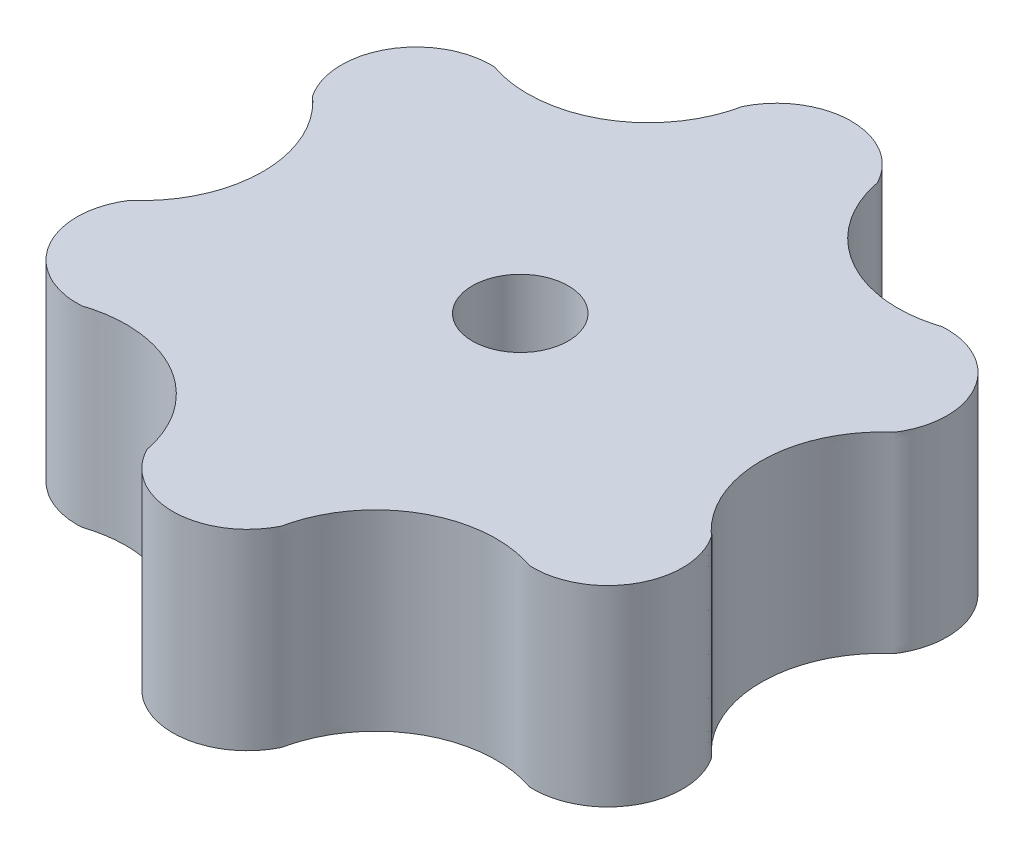
SolidWorks part; units mm, degrees
ref_plane "前视基准面" through (0, 0, 0) normal (0, 0, 1) x (1, 0, 0)
ref_plane "上视基准面" through (0, 0, 0) normal (0, 1, 0) x (1, 0, 0)
ref_plane "右视基准面" through (0, 0, 0) normal (1, 0, 0) x (0, 0, -1)
sketch "草图2" plane through (0, 0, 0) normal (0, -1, 0) x (1, 0, 0)
  spline S2 degree 3 poles (-0.0746, -0.0121) (0.0005, -0.0025) (0.0736, 0.0172) (0.1472, 0.0344) (0.2576, 0.0602) (0.368, 0.086) (0.5887, 0.1376) (0.732, 0.1865) (0.9487, 0.2533) (1.0214, 0.274) (1.1624, 0.3285) (1.3034, 0.383) (1.4444, 0.4375) (1.5854, 0.492) (1.6529, 0.5263) (1.8581, 0.6227) (1.9969, 0.6829) (2.2608, 0.8305) (2.3927, 0.9043) (2.5576, 0.9966) (2.5882, 1.0189) (2.6514, 1.0603) (2.7462, 1.1226) (2.8567, 1.1951) (2.9357, 1.247) (2.9673, 1.2677) (2.9838, 1.2771) (3.0288, 1.3115) (3.119, 1.3803) (3.2391, 1.4719) (3.3293, 1.5407) (3.3894, 1.5865) (3.4203, 1.6084) (3.5054, 1.6833) (3.6188, 1.7832) (3.7322, 1.8831) (3.8173, 1.958) (3.8457, 1.983) (3.8988, 2.0368) (3.9784, 2.1175) (4.058, 2.1982) (4.1642, 2.3058) (4.218, 2.3588) (4.3657, 2.5309) (4.4642, 2.6456) (4.5872, 2.7889) (4.6091, 2.8198) (4.6543, 2.8804) (4.722, 2.9713) (4.7898, 3.0621) (4.9253, 3.2439) (5.0046, 3.3728) (5.1275, 3.5633) (5.1698, 3.626) (5.2431, 3.7582) (5.3164, 3.8904) (5.3897, 4.0226) (5.4355, 4.1052) (5.437, 4.1246) (5.4448, 4.1616) (5.4567, 4.217) (5.4685, 4.2724) (5.5078, 4.4572) (5.5374, 4.6055) (5.6137, 4.8981) (5.6495, 5.045) (5.7746, 5.4808) (5.869, 5.7682) (6.1787, 6.6206) (6.4267, 7.1737) (6.7852, 7.839) (6.862, 7.9692) (6.9748, 8.1659) (7.0111, 8.2323) (7.0928, 8.3595) (7.1336, 8.4231) (7.2562, 8.6138) (7.3355, 8.7426) (7.5109, 8.9888) (7.5986, 9.1119) (7.774, 9.3581) (7.87, 9.4751) (8.0108, 9.6527) (8.0578, 9.7119) (8.1517, 9.8303) (8.2019, 9.887) (8.3518, 10.057) (8.4498, 10.1722) (8.6044, 10.338) (8.6557, 10.3936) (8.7614, 10.5016) (8.8143, 10.5556) (9.0787, 10.8255) (9.3006, 11.0312) (9.5859, 11.2789) (9.6419, 11.3298) (9.7585, 11.4259) (9.8168, 11.474) (9.9334, 11.5702) (9.9942, 11.6153) (10.1134, 11.7081) (10.1731, 11.7546) (10.3519, 11.8939) (10.4773, 11.9786) (10.6633, 12.1081) (10.7254, 12.1513) (10.8494, 12.2377) (10.9131, 12.2784) (11.1032, 12.402) (11.2333, 12.479) (11.4268, 12.5972) (11.4922, 12.6349) (11.6237, 12.7096) (11.6888, 12.7479) (11.889, 12.8544) (12.0218, 12.9267) (12.2253, 13.0267) (12.2931, 13.0601) (12.4287, 13.1268) (12.4974, 13.1582) (12.6349, 13.221) (12.7036, 13.2527) (12.8429, 13.3112) (12.9126, 13.3404) (13.1217, 13.4281) (13.2611, 13.4869) (13.5463, 13.5872) (13.6889, 13.6373) (13.9741, 13.7375) (14.1196, 13.7788) (14.4102, 13.862) (14.5548, 13.906) (14.7745, 13.9623) (14.8487, 13.977) (14.9962, 14.01) (15.1437, 14.0431) (15.2912, 14.0761) (15.4387, 14.1091) (15.5137, 14.1191) (15.7373, 14.1564) (15.8864, 14.1813) (16.1846, 14.231) (16.3355, 14.2431) (16.636, 14.2755) (16.7862, 14.2942) (17.0881, 14.3095) (17.2391, 14.3171) (17.541, 14.3324) (17.6922, 14.3313) (17.9189, 14.3301) (17.9945, 14.3297) (18.1457, 14.3288) (18.2212, 14.3248) (18.4478, 14.3169) (18.5986, 14.3063) (18.8249, 14.2925) (18.9, 14.2837) (19.0505, 14.2702) (19.1258, 14.2631) (19.2759, 14.2457) (19.3512, 14.2383) (19.5008, 14.2167) (19.5756, 14.2059) (19.8, 14.1736) (19.9494, 14.1507) (20.2459, 14.0918) (20.3947, 14.0649) (20.6897, 13.9987) (20.8359, 13.9602) (21.0557, 13.9045) (21.1292, 13.8868) (21.2748, 13.8462) (21.3466, 13.8226) (21.4911, 13.7782) (21.5994, 13.7448) (21.7258, 13.7059) (21.78, 13.6892) (21.8071, 13.6809) (21.8169, 13.6829) (21.8358, 13.6823) (21.9963, 13.6774) (22.1568, 13.6726) (22.3457, 13.6668) (22.3835, 13.6703) (22.459, 13.673) (22.5723, 13.6771) (22.6856, 13.6812) (22.7988, 13.6853) (22.8366, 13.6866) (22.9118, 13.6944) (23.0245, 13.7062) (23.1749, 13.7218) (23.2876, 13.7336) (23.3628, 13.7414) (23.4001, 13.7476) (23.5117, 13.7671) (23.6607, 13.793) (23.8096, 13.819) (23.9212, 13.8385) (23.9576, 13.8491) (24.031, 13.8672) (24.141, 13.8944) (24.2511, 13.9216) (24.3611, 13.9487) (24.3984, 13.9558) (24.4703, 13.979) (24.5782, 14.0138) (24.7221, 14.0602) (24.83, 14.095) (24.9019, 14.1182) (24.9381, 14.1291) (25.1134, 14.1996) (25.2536, 14.256) (25.4289, 14.3265) (25.4638, 14.341) (25.5318, 14.3741) (25.6337, 14.4237) (25.7356, 14.4734) (25.8715, 14.5395) (25.94, 14.5716) (26.0709, 14.6472) (26.2018, 14.7228) (26.3326, 14.7984) (26.4635, 14.874) (26.5248, 14.9185) (26.7126, 15.0455) (26.8404, 15.1267) (27.0783, 15.3132) (27.1972, 15.4065) (27.3459, 15.5231) (27.3724, 15.5502) (27.4285, 15.6009) (27.5126, 15.6769) (27.5967, 15.7529) (27.7649, 15.905) (27.867, 16.0166) (28.0242, 16.18) (28.0781, 16.2331) (28.1752, 16.3489) (28.2724, 16.4648) (28.3695, 16.5806) (28.4666, 16.6964) (28.5088, 16.7593) (28.5978, 16.8814) (28.6424, 16.9425) (28.7091, 17.0341) (28.7329, 17.0636) (28.7733, 17.1275) (28.8338, 17.2233) (28.8944, 17.3192) (28.9751, 17.447) (29.0163, 17.5104) (29.1244, 17.7097) (29.1965, 17.8425) (29.2776, 17.992) (29.2844, 18.0097) (29.3002, 18.044) (29.3238, 18.0956) (29.379, 18.2158) (29.4263, 18.3188) (29.4736, 18.4218) (29.4892, 18.4562) (29.516, 18.5269) (29.5562, 18.6329) (29.6098, 18.7742) (29.6501, 18.8802) (29.6769, 18.9508) (29.7097, 19.0593) (29.7645, 19.2402) (29.8083, 19.3848) (29.8411, 19.4933) (29.8476, 19.5307) (29.8645, 19.6044) (29.8897, 19.7149) (29.915, 19.8254) (29.9402, 19.9359) (29.9503, 19.9724) (29.962, 20.0471) (29.9794, 20.1591) (29.9969, 20.2711) (30.0202, 20.4205) (30.0348, 20.4948) (30.0539, 20.7207) (30.0666, 20.8713) (30.0825, 21.0596) (30.0849, 21.0973) (30.0859, 21.1729) (30.0875, 21.2862) (30.089, 21.3996) (30.091, 21.5507) (30.0929, 21.6263) (30.0843, 21.7772) (30.0756, 21.9281) (30.067, 22.079) (30.0583, 22.2299) (30.0458, 22.3046) (30.0169, 22.5295) (30.0015, 22.68) (29.9419, 22.9764) (29.9121, 23.1246) (29.8786, 23.2913) (29.8723, 23.3092) (29.8623, 23.3457) (29.8473, 23.4003) (29.8122, 23.5278) (29.7821, 23.6371) (29.722, 23.8557) (29.6679, 23.9971) (29.5928, 24.211) (29.5693, 24.2829) (29.5095, 24.4218) (29.4498, 24.5606) (29.39, 24.6994) (29.3302, 24.8383) (29.2928, 24.9041) (29.2238, 25.0386) (29.1892, 25.1058) (29.1375, 25.2067) (29.1216, 25.241) (29.0827, 25.3058) (29.0243, 25.403) (28.9465, 25.5326) (28.8881, 25.6298) (28.8589, 25.6784) (28.8514, 25.6964) (28.8233, 25.7217) (28.697, 25.8355) (28.5707, 25.9494) (28.4023, 26.1012) (28.3494, 26.1553) (28.2419, 26.2615) (28.1881, 26.3146) (28.0267, 26.4738) (27.9236, 26.5844) (27.4108, 27.1395) (27.0327, 27.6132) (26.6045, 28.236) (26.5233, 28.3635) (26.3998, 28.5536) (26.36, 28.6179) (26.2806, 28.7465) (26.2443, 28.8128) (26.1304, 29.0088) (26.053, 29.1388) (25.9144, 29.4074) (25.8451, 29.5418) (25.7412, 29.7433) (25.7105, 29.8124) (25.6478, 29.9499) (25.6164, 30.0186) (25.5536, 30.1561) (25.5205, 30.2241) (25.4615, 30.3633) (25.434, 30.4337) (25.3506, 30.6445) (25.293, 30.7843) (25.1895, 31.0684) (25.1431, 31.2122) (25.0467, 31.4987) (25.0036, 31.6437) (24.9426, 31.862) (24.9223, 31.9348) (24.8817, 32.0804) (24.8644, 32.154) (24.8279, 32.3007) (24.8105, 32.3742) (24.7776, 32.5218) (24.7595, 32.5952) (24.7164, 32.8178) (24.686, 32.9659) (24.6484, 33.1895) (24.6356, 33.264) (24.6148, 33.4137) (24.6044, 33.4885) (24.5732, 33.7131) (24.5545, 33.8631) (24.5354, 34.089) (24.529, 34.1643) (24.5162, 34.3149) (24.5081, 34.3901) (24.5, 34.5411) (24.4955, 34.6165) (24.4886, 34.7675) (24.4882, 34.8431) (24.4845, 34.9942) (24.4826, 35.0698) (24.4789, 35.2209) (24.4813, 35.2965) (24.4828, 35.5232) (24.4892, 35.6742) (24.4971, 35.9008) (24.503, 35.9762) (24.513, 36.127) (24.5171, 36.2025) (24.5351, 36.4285) (24.5515, 36.5788) (24.5896, 36.8787) (24.6076, 37.0288) (24.6541, 37.3275) (24.6832, 37.4758) (24.725, 37.6987) (24.7372, 37.7733) (24.7692, 37.921) (24.7856, 37.9948) (24.8405, 38.2148) (24.8771, 38.3614) (24.9504, 38.6547) (24.9953, 38.7991) (25.0607, 39.0162) (25.0829, 39.0884) (25.1305, 39.2319) (25.1531, 39.304) (25.2326, 39.5164) (25.2857, 39.6579) (25.3652, 39.8702) (25.3905, 39.9415) (25.4478, 40.0813) (25.4791, 40.1501) (25.5402, 40.2884) (25.5708, 40.3575) (25.6319, 40.4958) (25.6612, 40.5655) (25.759, 40.77) (25.8285, 40.9042) (25.9663, 41.1733) (26.0353, 41.3079) (26.1879, 41.5688) (26.2617, 41.7009) (26.3818, 41.8932) (26.4218, 41.9573) (26.5019, 42.0855) (26.5448, 42.1477) (26.6282, 42.2738) (26.6698, 42.3369) (26.7568, 42.4605) (26.8003, 42.5223) (26.9307, 42.7078) (27.0217, 42.8285) (27.2086, 43.0661) (27.3018, 43.1851) (27.4947, 43.4179) (27.5959, 43.5302) (27.7454, 43.7007) (27.796, 43.7568) (27.8984, 43.868) (27.9522, 43.9211) (28.1103, 44.0836) (28.2133, 44.1945) (28.4347, 44.4003) (28.5593, 44.516) (28.6908, 44.6382) (28.7116, 44.6575) (28.7254, 44.6703) (28.7306, 44.6782) (28.7554, 44.7184) (28.8151, 44.8148) (28.8946, 44.9433) (28.9542, 45.0397) (28.994, 45.104) (29.0121, 45.1372) (29.0652, 45.2373) (29.136, 45.3709) (29.2067, 45.5044) (29.251, 45.5879) (29.2576, 45.6057) (29.273, 45.6402) (29.2961, 45.6919) (29.35, 45.8127) (29.3962, 45.9162) (29.4424, 46.0198) (29.4581, 46.0542) (29.4841, 46.1251) (29.5231, 46.2316) (29.562, 46.338) (29.614, 46.48) (29.641, 46.5506) (29.704, 46.7684) (29.746, 46.9136) (29.809, 47.1314) (29.8217, 47.2061) (29.8534, 47.3539) (29.8773, 47.4647) (29.9011, 47.5755) (29.9169, 47.6494) (29.9204, 47.6872) (29.9363, 47.7994) (29.9523, 47.9117) (29.9682, 48.0239) (29.9788, 48.0987) (29.9864, 48.1359) (29.9944, 48.249) (30.005, 48.3998) (30.0157, 48.5505) (30.0236, 48.6636) (30.0275, 48.7013) (30.0275, 48.7768) (30.0275, 48.8902) (30.0274, 49.0036) (30.0274, 49.1547) (30.0302, 49.2304) (30.0141, 49.4566) (30.0034, 49.6073) (29.9873, 49.8335) (29.9757, 49.9082) (29.9544, 50.0578) (29.9384, 50.1701) (29.9224, 50.2823) (29.9117, 50.3571) (29.9042, 50.3941) (29.8804, 50.505) (29.8486, 50.6528) (29.8169, 50.8005) (29.7931, 50.9114) (29.7814, 50.9474) (29.7605, 51.02) (29.7291, 51.1289) (29.6977, 51.2379) (29.6662, 51.3468) (29.6577, 51.3837) (29.6318, 51.4547) (29.593, 51.5612) (29.5542, 51.6677) (29.5024, 51.8098) (29.4786, 51.8816) (29.3867, 52.0889) (29.3254, 52.227) (29.2335, 52.4343) (29.1955, 52.4998) (29.1252, 52.6336) (29.09, 52.7005) (28.9845, 52.9012) (28.902, 53.0281) (28.8033, 53.1891) (28.7835, 53.2214) (28.744, 53.2858) (28.7222, 53.3167) (28.6567, 53.4091) (28.5911, 53.5016) (28.5255, 53.5941) (28.4818, 53.6558) (28.4618, 53.688) (28.3901, 53.7758) (28.2946, 53.8929) (28.199, 54.01) (28.1273, 54.0979) (28.1034, 54.1271) (28.0517, 54.1823) (27.9742, 54.265) (27.8708, 54.3752) (27.7933, 54.4579) (27.7416, 54.5131) (27.7144, 54.5393) (27.5759, 54.6678) (27.4651, 54.7706) (27.3266, 54.8992) (27.2966, 54.9222) (27.2377, 54.9696) (27.1495, 55.0407) (27.0318, 55.1356) (26.9435, 55.2067) (26.8846, 55.2541) (26.8523, 55.2739) (26.7592, 55.3386) (26.6661, 55.4033) (26.5731, 55.4681) (26.511, 55.5112) (26.481, 55.5344) (26.3836, 55.5924) (26.2538, 55.6697) (26.1239, 55.7471) (26.0265, 55.8051) (25.9945, 55.8252) (25.9269, 55.8592) (25.8257, 55.9101) (25.7244, 55.9611) (25.5894, 56.029) (25.5229, 56.0653) (25.3137, 56.1527) (25.1742, 56.2109) (24.965, 56.2983) (24.893, 56.3212) (24.7497, 56.3695) (24.6423, 56.4057) (24.5349, 56.4419) (24.4633, 56.4661) (24.4267, 56.4756) (24.317, 56.5042) (24.1708, 56.5424) (24.0245, 56.5805) (23.9148, 56.6092) (23.8773, 56.6146) (23.803, 56.6286) (23.6916, 56.6495) (23.5802, 56.6704) (23.4688, 56.6914) (23.4319, 56.7) (23.3569, 56.7089) (23.2443, 56.7221) (23.1317, 56.7354) (22.9816, 56.753) (22.9067, 56.7637) (22.6802, 56.7749) (22.5292, 56.7824) (22.3405, 56.7917) (22.3027, 56.7901) (22.2272, 56.7888) (22.1138, 56.7868) (21.9816, 56.7845) (21.8777, 56.7827) (21.8494, 56.7822) (21.8352, 56.782) (21.8309, 56.7793) (21.8219, 56.7763) (21.7815, 56.7632) (21.6692, 56.7268) (21.5613, 56.6918) (21.4175, 56.6452) (21.3457, 56.6216) (21.2009, 56.5784) (21.1276, 56.5598) (20.909, 56.4997) (20.7634, 56.4589) (20.4685, 56.3923) (20.3213, 56.3577) (19.8767, 56.2688) (19.578, 56.221) (18.9783, 56.1442) (18.677, 56.1184) (18.2241, 56.0945) (18.0732, 56.0861) (17.8464, 56.0855) (17.7709, 56.0852) (17.6197, 56.0848) (17.5441, 56.083) (17.3174, 56.0877) (17.1665, 56.0971) (16.9778, 56.106) (16.9401, 56.1078) (16.8646, 56.1114) (16.8268, 56.1122) (16.7139, 56.123) (16.5634, 56.1374) (16.413, 56.1518) (16.2625, 56.1662) (16.1871, 56.172) (15.9628, 56.2052) (15.8133, 56.2273) (15.5142, 56.2716) (15.366, 56.3016) (15.1438, 56.3464) (15.0697, 56.3614) (14.9215, 56.3912) (14.8482, 56.4098) (14.7009, 56.4438) (14.6281, 56.464) (14.4817, 56.5016) (14.4082, 56.5194) (14.1903, 56.5819) (14.0452, 56.6244) (13.6126, 56.7603) (13.3273, 56.861) (12.9072, 57.0316) (12.7669, 57.0879) (12.559, 57.1784) (12.491, 57.2114) (12.3542, 57.2757) (12.2858, 57.3078) (12.0806, 57.4042) (11.9451, 57.4713) (11.6796, 57.616) (11.5455, 57.6858) (11.3499, 57.8005) (11.2847, 57.8387) (11.1543, 57.9151) (11.0908, 57.9561) (10.9626, 58.0362) (10.8977, 58.075) (10.7721, 58.1591) (10.7093, 58.2012) (10.5837, 58.2853) (10.5209, 58.3273) (10.3978, 58.415) (10.3362, 58.4588) (10.213, 58.5464) (10.1541, 58.5939) (10.0338, 58.6853) (9.9736, 58.7311) (9.7931, 58.8682) (9.6782, 58.9665) (9.4488, 59.1634) (9.3328, 59.2605) (9.109, 59.4637) (9.0022, 59.5707) (8.8392, 59.7283) (8.7848, 59.7808) (8.6761, 59.8858) (8.6258, 59.9423) (8.4723, 60.1092) (8.3699, 60.2204) (8.1652, 60.4428) (8.071, 60.5611) (7.9269, 60.7362) (7.8789, 60.7945) (7.7828, 60.9112) (7.7345, 60.9694) (7.6008, 61.1525) (7.5116, 61.2745) (7.3778, 61.4576) (7.334, 61.5191) (7.2485, 61.6438) (7.2081, 61.7077) (7.0849, 61.898) (7.0018, 62.0243) (6.8452, 62.2829) (6.7712, 62.4147) (6.6215, 62.6773) (6.5495, 62.8103) (6.4483, 63.0132) (6.4145, 63.0808) (6.347, 63.2161) (6.3152, 63.2846) (6.2516, 63.4217) (6.2183, 63.4896) (6.1583, 63.6283) (6.1283, 63.6977) (6.0382, 63.9058) (5.9848, 64.0473) (5.8726, 64.328) (5.8252, 64.4716) (5.728, 64.7578) (5.6779, 64.9006) (5.5956, 65.1915) (5.5545, 65.3369) (5.4927, 65.5551) (5.4762, 65.6288) (5.4425, 65.7762) (5.4087, 65.9235) (5.375, 66.0709) (5.356, 66.1537) (5.3541, 66.163) (5.3452, 66.1797) (5.3318, 66.2046) (5.3005, 66.2629) (5.2379, 66.3794) (5.1842, 66.4792) (5.1305, 66.5791) (5.113, 66.6126) (5.0729, 66.6766) (5.0127, 66.7727) (4.9324, 66.9008) (4.8722, 66.9968) (4.8321, 67.0609) (4.81, 67.0915) (4.6991, 67.2445) (4.6103, 67.3668) (4.4994, 67.5198) (4.4734, 67.5474) (4.4249, 67.6054) (4.3522, 67.6923) (4.2795, 67.7793) (4.1341, 67.9533) (4.0262, 68.0594) (3.8691, 68.2229) (3.8181, 68.2789) (3.706, 68.3802) (3.5939, 68.4816) (3.4818, 68.583) (3.3697, 68.6844) (3.309, 68.7295) (3.19, 68.8228) (3.1008, 68.8927) (3.0115, 68.9626) (2.9521, 69.0093) (2.9205, 69.0301) (2.7639, 69.1358) (2.6387, 69.2204) (2.4821, 69.3262) (2.4486, 69.3438) (2.3831, 69.3816) (2.285, 69.4383) (2.154, 69.5138) (2.0558, 69.5704) (2.0067, 69.5988) (1.9892, 69.606) (1.9552, 69.6225) (1.8703, 69.6638) (1.7513, 69.7217) (1.6494, 69.7712) (1.5814, 69.8043) (1.5481, 69.8224) (1.4429, 69.8646) (1.3027, 69.921) (1.1624, 69.9774) (1.0572, 70.0196) (1.0223, 70.0341) (0.9504, 70.0573) (0.8425, 70.0921) (0.7346, 70.1269) (0.5907, 70.1733) (0.5192, 70.1978) (0.2991, 70.2523) (0.1524, 70.2887) (-0.0677, 70.3432) (-0.1428, 70.3532) (-0.2917, 70.3793) (-0.3661, 70.3924) (-0.5894, 70.4317) (-0.7401, 70.4449) (-0.9655, 70.4689) (-1.0406, 70.4788) (-1.1916, 70.4848) (-1.3426, 70.4908) (-1.4936, 70.4968) (-1.6069, 70.5013) (-1.6447, 70.4988) (-1.7203, 70.4968) (-1.8336, 70.4938) (-1.9469, 70.4908) (-2.0602, 70.4878) (-2.098, 70.4869) (-2.1733, 70.4798) (-2.2861, 70.4693) (-2.4366, 70.4552) (-2.5495, 70.4447) (-2.6247, 70.4376) (-2.662, 70.4314) (-2.8485, 70.4011) (-2.9977, 70.3769) (-3.1656, 70.3496) (-3.1837, 70.3441) (-3.2205, 70.3355) (-3.2757, 70.3226) (-3.4045, 70.2925) (-3.5149, 70.2667) (-3.7357, 70.2151) (-3.8789, 70.1661) (-4.0956, 70.0994) (-4.1684, 70.0787) (-4.3093, 70.0242) (-4.4503, 69.9697) (-4.5913, 69.9152) (-4.7323, 69.8607) (-4.7998, 69.8264) (-5.005, 69.73) (-5.1439, 69.6697) (-5.4077, 69.5221) (-5.5396, 69.4483) (-5.7045, 69.3561) (-5.7351, 69.3338) (-5.7983, 69.2923) (-5.8931, 69.2301) (-6.0036, 69.1575) (-6.0826, 69.1057) (-6.1142, 69.085) (-6.1307, 69.0755) (-6.1757, 69.0412) (-6.2659, 68.9724) (-6.3861, 68.8807) (-6.4762, 68.812) (-6.5363, 68.7662) (-6.5672, 68.7443) (-6.6523, 68.6694) (-6.7657, 68.5695) (-6.8791, 68.4696) (-6.9642, 68.3946) (-6.9926, 68.3697) (-7.0457, 68.3159) (-7.1253, 68.2352) (-7.2049, 68.1545) (-7.3111, 68.0469) (-7.365, 67.9938) (-7.5126, 67.8218) (-7.6111, 67.7071) (-7.7341, 67.5637) (-7.756, 67.5329) (-7.8012, 67.4723) (-7.869, 67.3814) (-7.9367, 67.2905) (-8.0723, 67.1088) (-8.1516, 66.9799) (-8.2745, 66.7894) (-8.3168, 66.7267) (-8.3901, 66.5945) (-8.4634, 66.4623) (-8.5367, 66.3301) (-8.5825, 66.2475) (-8.5839, 66.2281) (-8.5918, 66.1911) (-8.6036, 66.1357) (-8.6154, 66.0802) (-8.6548, 65.8955) (-8.6843, 65.7471) (-8.7606, 65.4546) (-8.7964, 65.3077) (-8.9215, 64.8719) (-9.0159, 64.5845) (-9.3256, 63.7321) (-9.5737, 63.179) (-9.9321, 62.5137) (-10.009, 62.3835) (-10.1217, 62.1868) (-10.158, 62.1204) (-10.2397, 61.9932) (-10.2805, 61.9296) (-10.4031, 61.7388) (-10.4824, 61.6101) (-10.6578, 61.3639) (-10.7455, 61.2407) (-10.9209, 60.9945) (-11.0169, 60.8776) (-11.1578, 60.7) (-11.2047, 60.6408) (-11.2987, 60.5223) (-11.3488, 60.4657) (-11.4987, 60.2956) (-11.5968, 60.1805) (-11.7514, 60.0147) (-11.8026, 59.9591) (-11.9084, 59.8511) (-11.9612, 59.7971) (-12.2257, 59.5271) (-12.4475, 59.3215) (-12.7329, 59.0737) (-12.7888, 59.0229) (-12.9054, 58.9267) (-12.9637, 58.8786) (-13.0803, 58.7824) (-13.1411, 58.7374) (-13.2603, 58.6445) (-13.32, 58.5981) (-13.4989, 58.4588) (-13.6242, 58.3741) (-13.8103, 58.2446) (-13.8723, 58.2014) (-13.9963, 58.115) (-14.06, 58.0743) (-14.2501, 57.9507) (-14.3802, 57.8737) (-14.5737, 57.7555) (-14.6392, 57.7177) (-14.7706, 57.643) (-14.8357, 57.6047) (-15.036, 57.4983) (-15.1687, 57.426) (-15.3722, 57.3259) (-15.44, 57.2926) (-15.5756, 57.2259) (-15.6444, 57.1945) (-15.7818, 57.1316) (-15.8505, 57.1) (-15.9899, 57.0415) (-16.0595, 57.0123) (-16.2686, 56.9245) (-16.408, 56.8657) (-16.6932, 56.7655) (-16.8358, 56.7154) (-17.121, 56.6152) (-17.2665, 56.5739) (-17.5571, 56.4907) (-17.7018, 56.4466) (-17.9214, 56.3903) (-17.9956, 56.3757) (-18.1431, 56.3426) (-18.2906, 56.3096) (-18.4381, 56.2766) (-18.5856, 56.2435) (-18.6606, 56.2335) (-18.8842, 56.1962) (-19.0333, 56.1714) (-19.3315, 56.1217) (-19.4824, 56.1095) (-19.7829, 56.0771) (-19.9331, 56.0585) (-20.235, 56.0432) (-20.386, 56.0356) (-20.6879, 56.0203) (-20.8391, 56.0213) (-21.0659, 56.0226) (-21.1414, 56.023) (-21.2926, 56.0238) (-21.3681, 56.0279) (-21.5947, 56.0357) (-21.7455, 56.0464) (-21.9718, 56.0601) (-22.0469, 56.069) (-22.1975, 56.0825) (-22.2727, 56.0896) (-22.4228, 56.1069) (-22.4981, 56.1143) (-22.6477, 56.1359) (-22.7225, 56.1467) (-22.9469, 56.1791) (-23.0963, 56.202) (-23.3929, 56.2609) (-23.5417, 56.2877) (-23.8366, 56.3539) (-23.9828, 56.3925) (-24.2026, 56.4481) (-24.2761, 56.4659) (-24.4217, 56.5065) (-24.4935, 56.53) (-24.638, 56.5745) (-24.7463, 56.6078) (-24.8727, 56.6467) (-24.9269, 56.6634) (-24.954, 56.6717) (-24.9638, 56.6697) (-24.9827, 56.6703) (-25.1432, 56.6752) (-25.3038, 56.6801) (-25.4926, 56.6859) (-25.5304, 56.6824) (-25.6059, 56.6797) (-25.7192, 56.6756) (-25.8325, 56.6715) (-25.9458, 56.6673) (-25.9835, 56.6661) (-26.0587, 56.6583) (-26.1715, 56.6465) (-26.3218, 56.6308) (-26.4345, 56.619) (-26.5097, 56.6112) (-26.547, 56.605) (-26.6587, 56.5856) (-26.8076, 56.5596) (-26.9565, 56.5337) (-27.0682, 56.5142) (-27.1045, 56.5036) (-27.1779, 56.4854) (-27.2879, 56.4583) (-27.398, 56.4311) (-27.5081, 56.4039) (-27.5453, 56.3969) (-27.6172, 56.3737) (-27.7251, 56.3389) (-27.869, 56.2925) (-27.9769, 56.2577) (-28.0488, 56.2345) (-28.085, 56.2235) (-28.2603, 56.153) (-28.4005, 56.0966) (-28.5758, 56.0261) (-28.6107, 56.0116) (-28.6787, 55.9785) (-28.7806, 55.9289) (-28.8825, 55.8793) (-29.0184, 55.8131) (-29.0869, 55.7811) (-29.2178, 55.7055) (-29.3487, 55.6299) (-29.4796, 55.5542) (-29.6104, 55.4786) (-29.6717, 55.4342) (-29.8595, 55.3072) (-29.9873, 55.226) (-30.2252, 55.0394) (-30.3441, 54.9462) (-30.4928, 54.8296) (-30.5194, 54.8025) (-30.5754, 54.7518) (-30.6595, 54.6758) (-30.7436, 54.5997) (-30.9118, 54.4477) (-31.0139, 54.336) (-31.1711, 54.1727) (-31.2251, 54.1196) (-31.3222, 54.0037) (-31.4193, 53.8879) (-31.5164, 53.7721) (-31.6135, 53.6563) (-31.6557, 53.5934) (-31.7448, 53.4712) (-31.7893, 53.4102) (-31.8561, 53.3186) (-31.8799, 53.2891) (-31.9202, 53.2252) (-31.9808, 53.1293) (-32.0413, 53.0335) (-32.122, 52.9057) (-32.1632, 52.8423) (-32.2713, 52.643) (-32.3434, 52.5101) (-32.4245, 52.3607) (-32.4313, 52.343) (-32.4471, 52.3086) (-32.4708, 52.2571) (-32.5259, 52.1369) (-32.5732, 52.0339) (-32.6205, 51.9309) (-32.6361, 51.8965) (-32.6629, 51.8258) (-32.7031, 51.7198) (-32.7568, 51.5785) (-32.797, 51.4725) (-32.8238, 51.4018) (-32.8567, 51.2933) (-32.9114, 51.1125) (-32.9552, 50.9678) (-32.9881, 50.8593) (-32.9946, 50.822) (-33.0114, 50.7483) (-33.0367, 50.6378) (-33.0619, 50.5273) (-33.0872, 50.4168) (-33.0973, 50.3803) (-33.1089, 50.3056) (-33.1264, 50.1936) (-33.1438, 50.0816) (-33.1671, 49.9322) (-33.1818, 49.8579) (-33.2008, 49.632) (-33.2136, 49.4814) (-33.2294, 49.2931) (-33.2319, 49.2554) (-33.2329, 49.1798) (-33.2344, 49.0665) (-33.2359, 48.9531) (-33.238, 48.802) (-33.2399, 48.7264) (-33.2312, 48.5755) (-33.2226, 48.4246) (-33.2139, 48.2737) (-33.2052, 48.1228) (-33.1928, 48.0481) (-33.1638, 47.8232) (-33.1485, 47.6726) (-33.0889, 47.3763) (-33.0591, 47.2281) (-33.0256, 47.0614) (-33.0193, 47.0435) (-33.0093, 47.007) (-32.9942, 46.9524) (-32.9592, 46.8249) (-32.9291, 46.7155) (-32.869, 46.4969) (-32.8149, 46.3556) (-32.7397, 46.1417) (-32.7162, 46.0698) (-32.6565, 45.9309) (-32.5967, 45.7921) (-32.5369, 45.6532) (-32.4772, 45.5144) (-32.4397, 45.4486) (-32.3707, 45.3141) (-32.3362, 45.2468) (-32.2844, 45.146) (-32.2685, 45.1116) (-32.2296, 45.0468) (-32.1712, 44.9497) (-32.0934, 44.8201) (-32.035, 44.7229) (-32.0058, 44.6743) (-31.9984, 44.6563) (-31.9703, 44.631) (-31.844, 44.5171) (-31.7177, 44.4033) (-31.5493, 44.2515) (-31.4964, 44.1974) (-31.3888, 44.0912) (-31.335, 44.0381) (-31.1737, 43.8788) (-31.0706, 43.7683) (-30.5577, 43.2131) (-30.1797, 42.7395) (-29.7515, 42.1167) (-29.6703, 41.9892) (-29.5467, 41.7991) (-29.507, 41.7348) (-29.4276, 41.6062) (-29.3913, 41.5399) (-29.2773, 41.3439) (-29.1999, 41.2139) (-29.0614, 40.9452) (-28.9921, 40.8109) (-28.8882, 40.6094) (-28.8575, 40.5403) (-28.7947, 40.4028) (-28.7633, 40.3341) (-28.7006, 40.1966) (-28.6675, 40.1286) (-28.6085, 39.9894) (-28.5809, 39.919) (-28.4975, 39.7082) (-28.4399, 39.5684) (-28.3365, 39.2843) (-28.2873, 39.1414) (-28.1478, 38.7099) (-28.0662, 38.4187) (-27.9748, 38.052) (-27.9574, 37.9785) (-27.9245, 37.8309) (-27.9064, 37.7575) (-27.8633, 37.5349) (-27.8329, 37.3868) (-27.7954, 37.1632) (-27.7826, 37.0887) (-27.7618, 36.939) (-27.7514, 36.8642) (-27.7202, 36.6396) (-27.7015, 36.4896) (-27.6823, 36.2637) (-27.6759, 36.1884) (-27.6632, 36.0378) (-27.655, 35.9626) (-27.647, 35.8116) (-27.6424, 35.7362) (-27.6355, 35.5852) (-27.6352, 35.5096) (-27.6314, 35.3585) (-27.6296, 35.2829) (-27.6258, 35.1318) (-27.6283, 35.0562) (-27.6298, 34.8295) (-27.6361, 34.6785) (-27.6441, 34.4519) (-27.6499, 34.3765) (-27.66, 34.2257) (-27.6641, 34.1502) (-27.682, 33.9242) (-27.6984, 33.7739) (-27.7365, 33.474) (-27.7545, 33.3239) (-27.8011, 33.0252) (-27.8301, 32.8769) (-27.872, 32.654) (-27.8841, 32.5794) (-27.9162, 32.4317) (-27.9325, 32.3579) (-27.9874, 32.1379) (-28.0241, 31.9913) (-28.079, 31.7713) (-28.0985, 31.6983) (-28.1437, 31.554) (-28.1888, 31.4098) (-28.234, 31.2655) (-28.2791, 31.1213) (-28.3001, 31.0486) (-28.3796, 30.8363) (-28.4326, 30.6947) (-28.5121, 30.4824) (-28.5375, 30.4112) (-28.5948, 30.2713) (-28.626, 30.2025) (-28.6872, 30.0642) (-28.7177, 29.9951) (-28.7788, 29.8569) (-28.8081, 29.7872) (-28.906, 29.5826) (-28.9755, 29.4484) (-29.1132, 29.1793) (-29.1823, 29.0448) (-29.3349, 28.7838) (-29.4086, 28.6518) (-29.5287, 28.4595) (-29.5688, 28.3954) (-29.6488, 28.2672) (-29.6918, 28.2049) (-29.7752, 28.0788) (-29.8168, 28.0158) (-29.9037, 27.8921) (-29.9472, 27.8303) (-30.0777, 27.6449) (-30.1686, 27.5241) (-30.3556, 27.2866) (-30.4488, 27.1675) (-30.6417, 26.9348) (-30.7429, 26.8225) (-30.8923, 26.652) (-30.943, 26.5958) (-31.0454, 26.4847) (-31.0992, 26.4315) (-31.2573, 26.269) (-31.3602, 26.1581) (-31.5817, 25.9524) (-31.7063, 25.8366) (-31.8378, 25.7145) (-31.8585, 25.6952) (-31.8724, 25.6823) (-31.8775, 25.6744) (-31.9024, 25.6343) (-31.962, 25.5379) (-32.0415, 25.4093) (-32.1012, 25.3129) (-32.141, 25.2486) (-32.159, 25.2155) (-32.2121, 25.1153) (-32.2829, 24.9818) (-32.3537, 24.8482) (-32.3979, 24.7647) (-32.4046, 24.747) (-32.42, 24.7125) (-32.4431, 24.6607) (-32.497, 24.5399) (-32.5432, 24.4364) (-32.5893, 24.3329) (-32.6051, 24.2985) (-32.631, 24.2275) (-32.67, 24.1211) (-32.709, 24.0146) (-32.761, 23.8727) (-32.7879, 23.802) (-32.8509, 23.5842) (-32.8929, 23.439) (-32.9559, 23.2212) (-32.9686, 23.1465) (-33.0004, 22.9988) (-33.0242, 22.8879) (-33.048, 22.7771) (-33.0639, 22.7032) (-33.0673, 22.6654) (-33.0833, 22.5532) (-33.0992, 22.441) (-33.1152, 22.3287) (-33.1258, 22.2539) (-33.1334, 22.2167) (-33.1413, 22.1037) (-33.152, 21.9529) (-33.1626, 21.8021) (-33.1706, 21.689) (-33.1745, 21.6514) (-33.1744, 21.5758) (-33.1744, 21.4624) (-33.1744, 21.3491) (-33.1743, 21.1979) (-33.1771, 21.1222) (-33.161, 20.8961) (-33.1503, 20.7453) (-33.1342, 20.5192) (-33.1226, 20.4444) (-33.1013, 20.2948) (-33.0853, 20.1826) (-33.0693, 20.0703) (-33.0587, 19.9955) (-33.0511, 19.9585) (-33.0273, 19.8477) (-32.9956, 19.6999) (-32.9638, 19.5521) (-32.9401, 19.4412) (-32.9284, 19.4052) (-32.9074, 19.3326) (-32.876, 19.2237) (-32.8446, 19.1148) (-32.8132, 19.0059) (-32.8046, 18.9689) (-32.7787, 18.8979) (-32.7399, 18.7914) (-32.7011, 18.6849) (-32.6493, 18.5429) (-32.6255, 18.4711) (-32.5336, 18.2638) (-32.4724, 18.1256) (-32.3805, 17.9183) (-32.3425, 17.8528) (-32.2721, 17.719) (-32.237, 17.6521) (-32.1315, 17.4514) (-32.049, 17.3246) (-31.9502, 17.1635) (-31.9304, 17.1313) (-31.8909, 17.0669) (-31.8692, 17.036) (-31.8036, 16.9435) (-31.738, 16.851) (-31.6724, 16.7585) (-31.6287, 16.6969) (-31.6087, 16.6646) (-31.5371, 16.5768) (-31.4415, 16.4597) (-31.3459, 16.3426) (-31.2742, 16.2548) (-31.2503, 16.2255) (-31.1986, 16.1704) (-31.1211, 16.0877) (-31.0177, 15.9774) (-30.9402, 15.8947) (-30.8885, 15.8396) (-30.8613, 15.8134) (-30.7228, 15.6848) (-30.612, 15.582) (-30.4736, 15.4535) (-30.4435, 15.4305) (-30.3847, 15.3831) (-30.2964, 15.3119) (-30.1787, 15.2171) (-30.0904, 15.146) (-30.0316, 15.0986) (-29.9992, 15.0788) (-29.9061, 15.0141) (-29.8131, 14.9493) (-29.72, 14.8846) (-29.658, 14.8414) (-29.628, 14.8182) (-29.5306, 14.7602) (-29.4007, 14.6829) (-29.2708, 14.6056) (-29.1734, 14.5476) (-29.1414, 14.5275) (-29.0739, 14.4935) (-28.9726, 14.4425) (-28.8713, 14.3916) (-28.7363, 14.3236) (-28.6699, 14.2873) (-28.4607, 14.2) (-28.3212, 14.1417) (-28.112, 14.0543) (-28.0399, 14.0314) (-27.8966, 13.9831) (-27.7892, 13.9469) (-27.6818, 13.9107) (-27.6102, 13.8866) (-27.5736, 13.877) (-27.4639, 13.8484) (-27.3177, 13.8103) (-27.1714, 13.7721) (-27.0617, 13.7435) (-27.0242, 13.738) (-26.95, 13.7241) (-26.8386, 13.7031) (-26.7271, 13.6822) (-26.6157, 13.6613) (-26.5788, 13.6526) (-26.5038, 13.6438) (-26.3912, 13.6305) (-26.2786, 13.6173) (-26.1285, 13.5996) (-26.0536, 13.5889) (-25.8271, 13.5778) (-25.6762, 13.5703) (-25.4875, 13.561) (-25.4497, 13.5626) (-25.3741, 13.5639) (-25.2608, 13.5659) (-25.1285, 13.5682) (-25.0246, 13.57) (-24.9963, 13.5704) (-24.9821, 13.5707) (-24.9778, 13.5734) (-24.9688, 13.5763) (-24.9284, 13.5894) (-24.8161, 13.6259) (-24.7082, 13.6609) (-24.5645, 13.7075) (-24.4927, 13.7311) (-24.3478, 13.7743) (-24.2745, 13.7929) (-24.0559, 13.853) (-23.9103, 13.8938) (-23.6154, 13.9604) (-23.4683, 13.9949) (-23.0236, 14.0839) (-22.725, 14.1317) (-22.1252, 14.2085) (-21.8239, 14.2343) (-21.3711, 14.2582) (-21.2201, 14.2665) (-20.9934, 14.2672) (-20.9178, 14.2674) (-20.7666, 14.2679) (-20.691, 14.2696) (-20.4644, 14.265) (-20.3135, 14.2556) (-20.1247, 14.2466) (-20.087, 14.2448) (-20.0115, 14.2412) (-19.9737, 14.2405) (-19.8608, 14.2297) (-19.7104, 14.2153) (-19.5599, 14.2009) (-19.4094, 14.1865) (-19.334, 14.1806) (-19.1097, 14.1474) (-18.9602, 14.1253) (-18.6612, 14.0811) (-18.513, 14.051) (-18.2907, 14.0062) (-18.2166, 13.9913) (-18.0685, 13.9614) (-17.9951, 13.9429) (-17.8479, 13.9089) (-17.775, 13.8887) (-17.6286, 13.8511) (-17.5551, 13.8333) (-17.3372, 13.7708) (-17.1922, 13.7282) (-16.7595, 13.5924) (-16.4743, 13.4916) (-16.0541, 13.3211) (-15.9138, 13.2648) (-15.7059, 13.1742) (-15.638, 13.1412) (-15.5011, 13.077) (-15.4327, 13.0448) (-15.2275, 12.9485) (-15.092, 12.8813) (-14.8266, 12.7367) (-14.6924, 12.6669) (-14.4968, 12.5522) (-14.4317, 12.5139) (-14.3013, 12.4375) (-14.2377, 12.3965) (-14.1095, 12.3164) (-14.0446, 12.2777) (-13.919, 12.1935) (-13.8562, 12.1515) (-13.7307, 12.0674) (-13.6679, 12.0253) (-13.5447, 11.9377) (-13.4831, 11.8939) (-13.36, 11.8062) (-13.3011, 11.7588) (-13.1807, 11.6673) (-13.1206, 11.6216) (-12.94, 11.4844) (-12.8251, 11.3861) (-12.5957, 11.1892) (-12.4798, 11.0922) (-12.256, 10.8889) (-12.1491, 10.7819) (-11.9861, 10.6244) (-11.9318, 10.5718) (-11.8231, 10.4668) (-11.7728, 10.4103) (-11.6192, 10.2435) (-11.5169, 10.1323) (-11.3121, 9.9098) (-11.2179, 9.7915) (-11.0738, 9.6165) (-11.0258, 9.5581) (-10.9297, 9.4414) (-10.8815, 9.3832) (-10.7477, 9.2001) (-10.6585, 9.0781) (-10.5247, 8.895) (-10.4809, 8.8335) (-10.3954, 8.7088) (-10.355, 8.645) (-10.2318, 8.4546) (-10.1487, 8.3283) (-9.9921, 8.0697) (-9.9181, 7.9379) (-9.7684, 7.6753) (-9.6964, 7.5423) (-9.5952, 7.3394) (-9.5615, 7.2718) (-9.494, 7.1366) (-9.4621, 7.0681) (-9.3985, 6.9309) (-9.3653, 6.863) (-9.3052, 6.7243) (-9.2752, 6.6549) (-9.1851, 6.4469) (-9.1318, 6.3054) (-9.0196, 6.0247) (-8.9721, 5.881) (-8.8749, 5.5948) (-8.8249, 5.4521) (-8.7425, 5.1612) (-8.7014, 5.0157) (-8.6397, 4.7976) (-8.6231, 4.7238) (-8.5894, 4.5765) (-8.5557, 4.4291) (-8.522, 4.2818) (-8.503, 4.1989) (-8.5011, 4.1896) (-8.4921, 4.173) (-8.4787, 4.148) (-8.4474, 4.0898) (-8.3848, 3.9733) (-8.3311, 3.8734) (-8.2775, 3.7735) (-8.26, 3.74) (-8.2198, 3.676) (-8.1596, 3.5799) (-8.0794, 3.4519) (-8.0192, 3.3558) (-7.979, 3.2918) (-7.9569, 3.2611) (-7.846, 3.1082) (-7.7572, 2.9858) (-7.6463, 2.8329) (-7.6203, 2.8053) (-7.5718, 2.7473) (-7.4991, 2.6603) (-7.4264, 2.5733) (-7.281, 2.3993) (-7.1731, 2.2932) (-7.016, 2.1297) (-6.9651, 2.0738) (-6.8529, 1.9724) (-6.7408, 1.871) (-6.6287, 1.7696) (-6.5166, 1.6683) (-6.4559, 1.6231) (-6.3369, 1.5299) (-6.2477, 1.4599) (-6.1585, 1.39) (-6.099, 1.3434) (-6.0674, 1.3226) (-5.9109, 1.2168) (-5.7856, 1.1322) (-5.629, 1.0265) (-5.5955, 1.0088) (-5.5301, 0.971) (-5.4319, 0.9144) (-5.3009, 0.8389) (-5.2027, 0.7822) (-5.1537, 0.7539) (-5.1361, 0.7467) (-5.1021, 0.7301) (-5.0172, 0.6888) (-4.8982, 0.631) (-4.7963, 0.5814) (-4.7283, 0.5484) (-4.695, 0.5303) (-4.5898, 0.488) (-4.4496, 0.4317) (-4.3093, 0.3753) (-4.2041, 0.333) (-4.1692, 0.3186) (-4.0973, 0.2954) (-3.9894, 0.2606) (-3.8815, 0.2258) (-3.7377, 0.1793) (-3.6661, 0.1548) (-3.446, 0.1003) (-3.2993, 0.064) (-3.0792, 0.0095) (-3.0041, -0.0005) (-2.8553, -0.0267) (-2.7808, -0.0398) (-2.5575, -0.0791) (-2.4068, -0.0922) (-2.1814, -0.1163) (-2.1064, -0.1262) (-1.9553, -0.1322) (-1.8043, -0.1381) (-1.6533, -0.1441) (-1.54, -0.1486) (-1.5022, -0.1461) (-1.4267, -0.1441) (-1.3133, -0.1411) (-1.2, -0.1381) (-1.0867, -0.1351) (-1.0489, -0.1342) (-0.9737, -0.1272) (-0.8608, -0.1166) (-0.7103, -0.1026) (-0.5974, -0.092) (-0.5222, -0.085) (-0.4849, -0.0787) (-0.373, -0.0605) (-0.2611, -0.0424) (-0.1492, -0.0242) (-0.0746, -0.0121) (0.0005, -0.0025) (0.0736, 0.0172) knots -0.000977 -0.000488 -0.000488 0 0.000488 0.000488 0.000977 0.001953 0.001953 0.003906 0.003906 0.004883 0.004883 0.005859 0.006836 0.006836 0.007813 0.007813 0.009766 0.009766 0.011719 0.011719 0.012207 0.012207 0.012695 0.013672 0.013916 0.013916 0.01416 0.01416 0.014648 0.015625 0.016113 0.016113 0.016602 0.016602 0.017578 0.018555 0.018555 0.019043 0.019043 0.019531 0.020508 0.020508 0.021484 0.021484 0.023438 0.023438 0.023926 0.023926 0.024414 0.025391 0.025391 0.027344 0.027344 0.02832 0.02832 0.029297 0.030273 0.030273 0.030518 0.030518 0.030762 0.03125 0.03125 0.033203 0.033203 0.035156 0.035156 0.039063 0.039063 0.046875 0.046875 0.048828 0.048828 0.049805 0.049805 0.050781 0.050781 0.052734 0.052734 0.054688 0.054688 0.056641 0.056641 0.057617 0.057617 0.058594 0.058594 0.060547 0.060547 0.061523 0.061523 0.0625 0.0625 0.066406 0.066406 0.067383 0.067383 0.068359 0.068359 0.069336 0.069336 0.070313 0.070313 0.072266 0.072266 0.073242 0.073242 0.074219 0.074219 0.076172 0.076172 0.077148 0.077148 0.078125 0.078125 0.080078 0.080078 0.081055 0.081055 0.082031 0.082031 0.083008 0.083008 0.083984 0.083984 0.085938 0.085938 0.087891 0.087891 0.089844 0.089844 0.091797 0.091797 0.092773 0.092773 0.09375 0.094727 0.094727 0.095703 0.095703 0.097656 0.097656 0.099609 0.099609 0.101563 0.101563 0.103516 0.103516 0.105469 0.105469 0.106445 0.106445 0.107422 0.107422 0.109375 0.109375 0.110352 0.110352 0.111328 0.111328 0.112305 0.112305 0.113281 0.113281 0.115234 0.115234 0.117188 0.117188 0.119141 0.119141 0.120117 0.120117 0.121094 0.121094 0.12207 0.122559 0.122803 0.122803 0.122925 0.122925 0.123047 0.125 0.125 0.125488 0.125488 0.125977 0.126953 0.126953 0.127441 0.127441 0.12793 0.128906 0.129395 0.129395 0.129883 0.129883 0.130859 0.131836 0.131836 0.132324 0.132324 0.132813 0.133789 0.133789 0.134277 0.134277 0.134766 0.135742 0.13623 0.13623 0.136719 0.136719 0.138672 0.138672 0.13916 0.13916 0.139648 0.140625 0.140625 0.141602 0.141602 0.142578 0.143555 0.143555 0.144531 0.144531 0.146484 0.146484 0.148438 0.148438 0.148926 0.148926 0.149414 0.150391 0.150391 0.152344 0.152344 0.15332 0.15332 0.154297 0.155273 0.155273 0.15625 0.15625 0.157227 0.157227 0.157715 0.157715 0.158203 0.15918 0.15918 0.160156 0.160156 0.162109 0.162109 0.162354 0.162354 0.162598 0.163086 0.164063 0.164063 0.164551 0.164551 0.165039 0.166016 0.166504 0.166504 0.166992 0.167969 0.168945 0.168945 0.169434 0.169434 0.169922 0.170898 0.170898 0.171387 0.171387 0.171875 0.172852 0.172852 0.173828 0.173828 0.175781 0.175781 0.17627 0.17627 0.176758 0.177734 0.177734 0.178711 0.178711 0.179688 0.180664 0.180664 0.181641 0.181641 0.183594 0.183594 0.185547 0.185547 0.185791 0.185791 0.186035 0.186523 0.1875 0.1875 0.189453 0.189453 0.19043 0.19043 0.191406 0.192383 0.192383 0.193359 0.193359 0.194336 0.194336 0.194824 0.194824 0.195313 0.196289 0.196777 0.196777 0.197021 0.197021 0.197266 0.199219 0.199219 0.200195 0.200195 0.201172 0.201172 0.203125 0.203125 0.210938 0.210938 0.212891 0.212891 0.213867 0.213867 0.214844 0.214844 0.216797 0.216797 0.21875 0.21875 0.219727 0.219727 0.220703 0.220703 0.22168 0.22168 0.222656 0.222656 0.224609 0.224609 0.226563 0.226563 0.228516 0.228516 0.229492 0.229492 0.230469 0.230469 0.231445 0.231445 0.232422 0.232422 0.234375 0.234375 0.235352 0.235352 0.236328 0.236328 0.238281 0.238281 0.239258 0.239258 0.240234 0.240234 0.241211 0.241211 0.242188 0.242188 0.243164 0.243164 0.244141 0.244141 0.246094 0.246094 0.24707 0.24707 0.248047 0.248047 0.25 0.25 0.251953 0.251953 0.253906 0.253906 0.254883 0.254883 0.255859 0.255859 0.257813 0.257813 0.259766 0.259766 0.260742 0.260742 0.261719 0.261719 0.263672 0.263672 0.264648 0.264648 0.265625 0.265625 0.266602 0.266602 0.267578 0.267578 0.269531 0.269531 0.271484 0.271484 0.273438 0.273438 0.274414 0.274414 0.275391 0.275391 0.276367 0.276367 0.277344 0.277344 0.279297 0.279297 0.28125 0.28125 0.283203 0.283203 0.28418 0.28418 0.285156 0.285156 0.287109 0.287109 0.289063 0.289307 0.289429 0.289429 0.289551 0.289551 0.290039 0.291016 0.291504 0.291504 0.291992 0.291992 0.292969 0.293945 0.293945 0.294189 0.294189 0.294434 0.294922 0.295898 0.295898 0.296387 0.296387 0.296875 0.297852 0.297852 0.298828 0.298828 0.300781 0.300781 0.301758 0.301758 0.302734 0.303223 0.303223 0.303711 0.303711 0.304688 0.305176 0.305176 0.305664 0.305664 0.306641 0.307617 0.307617 0.308105 0.308105 0.308594 0.30957 0.30957 0.310547 0.310547 0.3125 0.3125 0.313477 0.313477 0.314453 0.314941 0.314941 0.31543 0.31543 0.316406 0.317383 0.317383 0.317871 0.317871 0.318359 0.319336 0.319336 0.319824 0.319824 0.320313 0.321289 0.321289 0.322266 0.322266 0.324219 0.324219 0.325195 0.325195 0.326172 0.326172 0.328125 0.328125 0.328613 0.328613 0.329102 0.329102 0.330078 0.330566 0.330566 0.331055 0.331055 0.332031 0.333008 0.333008 0.333496 0.333496 0.333984 0.334961 0.335449 0.335449 0.335938 0.335938 0.337891 0.337891 0.338379 0.338379 0.338867 0.339844 0.340332 0.340332 0.34082 0.34082 0.341797 0.342285 0.342285 0.342773 0.342773 0.34375 0.344727 0.344727 0.345215 0.345215 0.345703 0.34668 0.34668 0.347656 0.347656 0.349609 0.349609 0.350586 0.350586 0.351563 0.352051 0.352051 0.352539 0.352539 0.353516 0.354492 0.354492 0.35498 0.35498 0.355469 0.356445 0.356445 0.356934 0.356934 0.357422 0.358398 0.358398 0.359375 0.359375 0.361328 0.361328 0.361816 0.361816 0.362305 0.363281 0.363525 0.363647 0.363647 0.363708 0.363708 0.36377 0.364258 0.365234 0.365234 0.366211 0.366211 0.367188 0.367188 0.369141 0.369141 0.371094 0.371094 0.375 0.375 0.378906 0.378906 0.380859 0.380859 0.381836 0.381836 0.382813 0.382813 0.384766 0.384766 0.385254 0.385254 0.385742 0.385742 0.386719 0.387695 0.387695 0.388672 0.388672 0.390625 0.390625 0.392578 0.392578 0.393555 0.393555 0.394531 0.394531 0.395508 0.395508 0.396484 0.396484 0.398438 0.398438 0.402344 0.402344 0.404297 0.404297 0.405273 0.405273 0.40625 0.40625 0.408203 0.408203 0.410156 0.410156 0.411133 0.411133 0.412109 0.412109 0.413086 0.413086 0.414063 0.414063 0.415039 0.415039 0.416016 0.416016 0.416992 0.416992 0.417969 0.417969 0.419922 0.419922 0.421875 0.421875 0.423828 0.423828 0.424805 0.424805 0.425781 0.425781 0.427734 0.427734 0.429688 0.429688 0.430664 0.430664 0.431641 0.431641 0.433594 0.433594 0.43457 0.43457 0.435547 0.435547 0.4375 0.4375 0.439453 0.439453 0.441406 0.441406 0.442383 0.442383 0.443359 0.443359 0.444336 0.444336 0.445313 0.445313 0.447266 0.447266 0.449219 0.449219 0.451172 0.451172 0.453125 0.453125 0.454102 0.454102 0.455078 0.456055 0.456055 0.456177 0.456177 0.456299 0.456543 0.457031 0.458008 0.458008 0.458496 0.458496 0.458984 0.459961 0.460449 0.460449 0.460938 0.460938 0.462891 0.462891 0.463379 0.463379 0.463867 0.464844 0.464844 0.466797 0.466797 0.467773 0.467773 0.46875 0.469727 0.469727 0.470703 0.470703 0.47168 0.472168 0.472168 0.472656 0.472656 0.474609 0.474609 0.475098 0.475098 0.475586 0.476563 0.477051 0.477051 0.477295 0.477295 0.477539 0.478516 0.479004 0.479004 0.479492 0.479492 0.480469 0.481445 0.481445 0.481934 0.481934 0.482422 0.483398 0.483398 0.484375 0.484375 0.486328 0.486328 0.487305 0.487305 0.488281 0.488281 0.490234 0.490234 0.491211 0.491211 0.492188 0.493164 0.493164 0.493652 0.493652 0.494141 0.495117 0.495117 0.495605 0.495605 0.496094 0.49707 0.497559 0.497559 0.498047 0.498047 0.5 0.5 0.500244 0.500244 0.500488 0.500977 0.501953 0.501953 0.503906 0.503906 0.504883 0.504883 0.505859 0.506836 0.506836 0.507813 0.507813 0.509766 0.509766 0.511719 0.511719 0.512207 0.512207 0.512695 0.513672 0.513916 0.513916 0.51416 0.51416 0.514648 0.515625 0.516113 0.516113 0.516602 0.516602 0.517578 0.518555 0.518555 0.519043 0.519043 0.519531 0.520508 0.520508 0.521484 0.521484 0.523438 0.523438 0.523926 0.523926 0.524414 0.525391 0.525391 0.527344 0.527344 0.52832 0.52832 0.529297 0.530273 0.530273 0.530518 0.530518 0.530762 0.53125 0.53125 0.533203 0.533203 0.535156 0.535156 0.539063 0.539063 0.546875 0.546875 0.548828 0.548828 0.549805 0.549805 0.550781 0.550781 0.552734 0.552734 0.554688 0.554688 0.556641 0.556641 0.557617 0.557617 0.558594 0.558594 0.560547 0.560547 0.561523 0.561523 0.5625 0.5625 0.566406 0.566406 0.567383 0.567383 0.568359 0.568359 0.569336 0.569336 0.570313 0.570313 0.572266 0.572266 0.573242 0.573242 0.574219 0.574219 0.576172 0.576172 0.577148 0.577148 0.578125 0.578125 0.580078 0.580078 0.581055 0.581055 0.582031 0.582031 0.583008 0.583008 0.583984 0.583984 0.585938 0.585938 0.587891 0.587891 0.589844 0.589844 0.591797 0.591797 0.592773 0.592773 0.59375 0.594727 0.594727 0.595703 0.595703 0.597656 0.597656 0.599609 0.599609 0.601563 0.601563 0.603516 0.603516 0.605469 0.605469 0.606445 0.606445 0.607422 0.607422 0.609375 0.609375 0.610352 0.610352 0.611328 0.611328 0.612305 0.612305 0.613281 0.613281 0.615234 0.615234 0.617188 0.617188 0.619141 0.619141 0.620117 0.620117 0.621094 0.621094 0.62207 0.622559 0.622803 0.622803 0.622925 0.622925 0.623047 0.625 0.625 0.625488 0.625488 0.625977 0.626953 0.626953 0.627441 0.627441 0.62793 0.628906 0.629395 0.629395 0.629883 0.629883 0.630859 0.631836 0.631836 0.632324 0.632324 0.632813 0.633789 0.633789 0.634277 0.634277 0.634766 0.635742 0.63623 0.63623 0.636719 0.636719 0.638672 0.638672 0.63916 0.63916 0.639648 0.640625 0.640625 0.641602 0.641602 0.642578 0.643555 0.643555 0.644531 0.644531 0.646484 0.646484 0.648438 0.648438 0.648926 0.648926 0.649414 0.650391 0.650391 0.652344 0.652344 0.65332 0.65332 0.654297 0.655273 0.655273 0.65625 0.65625 0.657227 0.657227 0.657715 0.657715 0.658203 0.65918 0.65918 0.660156 0.660156 0.662109 0.662109 0.662354 0.662354 0.662598 0.663086 0.664063 0.664063 0.664551 0.664551 0.665039 0.666016 0.666504 0.666504 0.666992 0.667969 0.668945 0.668945 0.669434 0.669434 0.669922 0.670898 0.670898 0.671387 0.671387 0.671875 0.672852 0.672852 0.673828 0.673828 0.675781 0.675781 0.67627 0.67627 0.676758 0.677734 0.677734 0.678711 0.678711 0.679688 0.680664 0.680664 0.681641 0.681641 0.683594 0.683594 0.685547 0.685547 0.685791 0.685791 0.686035 0.686523 0.6875 0.6875 0.689453 0.689453 0.69043 0.69043 0.691406 0.692383 0.692383 0.693359 0.693359 0.694336 0.694336 0.694824 0.694824 0.695313 0.696289 0.696777 0.696777 0.697021 0.697021 0.697266 0.699219 0.699219 0.700195 0.700195 0.701172 0.701172 0.703125 0.703125 0.710938 0.710938 0.712891 0.712891 0.713867 0.713867 0.714844 0.714844 0.716797 0.716797 0.71875 0.71875 0.719727 0.719727 0.720703 0.720703 0.72168 0.72168 0.722656 0.722656 0.724609 0.724609 0.726563 0.726563 0.730469 0.730469 0.731445 0.731445 0.732422 0.732422 0.734375 0.734375 0.735352 0.735352 0.736328 0.736328 0.738281 0.738281 0.739258 0.739258 0.740234 0.740234 0.741211 0.741211 0.742188 0.742188 0.743164 0.743164 0.744141 0.744141 0.746094 0.746094 0.74707 0.74707 0.748047 0.748047 0.75 0.75 0.751953 0.751953 0.753906 0.753906 0.754883 0.754883 0.755859 0.755859 0.757813 0.757813 0.758789 0.758789 0.759766 0.760742 0.760742 0.761719 0.761719 0.763672 0.763672 0.764648 0.764648 0.765625 0.765625 0.766602 0.766602 0.767578 0.767578 0.769531 0.769531 0.771484 0.771484 0.773438 0.773438 0.774414 0.774414 0.775391 0.775391 0.776367 0.776367 0.777344 0.777344 0.779297 0.779297 0.78125 0.78125 0.783203 0.783203 0.78418 0.78418 0.785156 0.785156 0.787109 0.787109 0.789063 0.789307 0.789429 0.789429 0.789551 0.789551 0.790039 0.791016 0.791504 0.791504 0.791992 0.791992 0.792969 0.793945 0.793945 0.794189 0.794189 0.794434 0.794922 0.795898 0.795898 0.796387 0.796387 0.796875 0.797852 0.797852 0.798828 0.798828 0.800781 0.800781 0.801758 0.801758 0.802734 0.803223 0.803223 0.803711 0.803711 0.804688 0.805176 0.805176 0.805664 0.805664 0.806641 0.807617 0.807617 0.808105 0.808105 0.808594 0.80957 0.80957 0.810547 0.810547 0.8125 0.8125 0.813477 0.813477 0.814453 0.814941 0.814941 0.81543 0.81543 0.816406 0.817383 0.817383 0.817871 0.817871 0.818359 0.819336 0.819336 0.819824 0.819824 0.820313 0.821289 0.821289 0.822266 0.822266 0.824219 0.824219 0.825195 0.825195 0.826172 0.826172 0.828125 0.828125 0.828613 0.828613 0.829102 0.829102 0.830078 0.830566 0.830566 0.831055 0.831055 0.832031 0.833008 0.833008 0.833496 0.833496 0.833984 0.834961 0.835449 0.835449 0.835938 0.835938 0.837891 0.837891 0.838379 0.838379 0.838867 0.839844 0.840332 0.840332 0.84082 0.84082 0.841797 0.842285 0.842285 0.842773 0.842773 0.84375 0.844727 0.844727 0.845215 0.845215 0.845703 0.84668 0.84668 0.847656 0.847656 0.849609 0.849609 0.850586 0.850586 0.851563 0.852051 0.852051 0.852539 0.852539 0.853516 0.854492 0.854492 0.85498 0.85498 0.855469 0.856445 0.856445 0.856934 0.856934 0.857422 0.858398 0.858398 0.859375 0.859375 0.861328 0.861328 0.861816 0.861816 0.862305 0.863281 0.863525 0.863647 0.863647 0.863708 0.863708 0.86377 0.864258 0.865234 0.865234 0.866211 0.866211 0.867188 0.867188 0.869141 0.869141 0.871094 0.871094 0.875 0.875 0.878906 0.878906 0.880859 0.880859 0.881836 0.881836 0.882813 0.882813 0.884766 0.884766 0.885254 0.885254 0.885742 0.885742 0.886719 0.887695 0.887695 0.888672 0.888672 0.890625 0.890625 0.892578 0.892578 0.893555 0.893555 0.894531 0.894531 0.895508 0.895508 0.896484 0.896484 0.898438 0.898438 0.902344 0.902344 0.904297 0.904297 0.905273 0.905273 0.90625 0.90625 0.908203 0.908203 0.910156 0.910156 0.911133 0.911133 0.912109 0.912109 0.913086 0.913086 0.914063 0.914063 0.915039 0.915039 0.916016 0.916016 0.916992 0.916992 0.917969 0.917969 0.919922 0.919922 0.921875 0.921875 0.923828 0.923828 0.924805 0.924805 0.925781 0.925781 0.927734 0.927734 0.929688 0.929688 0.930664 0.930664 0.931641 0.931641 0.933594 0.933594 0.93457 0.93457 0.935547 0.935547 0.9375 0.9375 0.939453 0.939453 0.941406 0.941406 0.942383 0.942383 0.943359 0.943359 0.944336 0.944336 0.945313 0.945313 0.947266 0.947266 0.949219 0.949219 0.951172 0.951172 0.953125 0.953125 0.954102 0.954102 0.955078 0.956055 0.956055 0.956177 0.956177 0.956299 0.956543 0.957031 0.958008 0.958008 0.958496 0.958496 0.958984 0.959961 0.960449 0.960449 0.960938 0.960938 0.962891 0.962891 0.963379 0.963379 0.963867 0.964844 0.964844 0.966797 0.966797 0.967773 0.967773 0.96875 0.969727 0.969727 0.970703 0.970703 0.97168 0.972168 0.972168 0.972656 0.972656 0.974609 0.974609 0.975098 0.975098 0.975586 0.976563 0.977051 0.977051 0.977295 0.977295 0.977539 0.978516 0.979004 0.979004 0.979492 0.979492 0.980469 0.981445 0.981445 0.981934 0.981934 0.982422 0.983398 0.983398 0.984375 0.984375 0.986328 0.986328 0.987305 0.987305 0.988281 0.988281 0.990234 0.990234 0.991211 0.991211 0.992188 0.993164 0.993164 0.993652 0.993652 0.994141 0.995117 0.995117 0.995605 0.995605 0.996094 0.99707 0.997559 0.997559 0.998047 0.998047 0.999023 0.999512 0.999512 1 1.000488 1.000488 1.000977 only from (0, 0) to (0, 0)
extrude "凸台-拉伸1" add sketch "草图2" along normal blind 20
sketch "草图3" plane through (0, 0, 0) normal (0, 1, 0) x (1, 0, 0)
  line L0 (-39.4184, -34.4876) -> (37.6979, -34.4876) construction
  line L1 (-1.4016, 11.1825) -> (-1.4016, -82.9618) construction
  circle A0 centre (-1.4016, -34.4876) radius 5
  dimension "D1" = 10
extrude "切除-拉伸1" cut sketch "草图3" against normal through all
